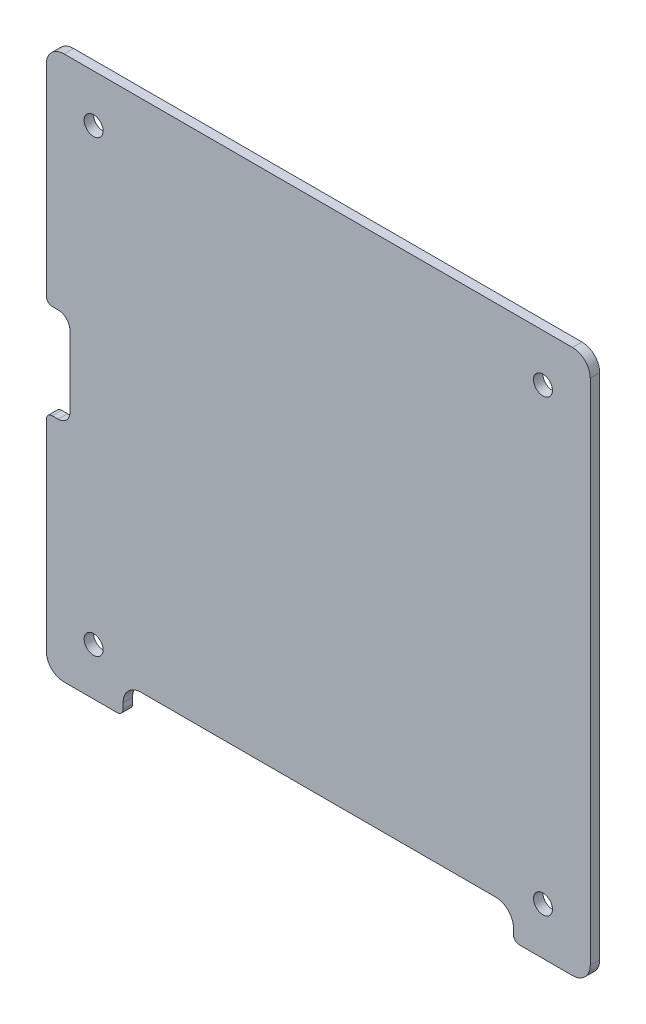
SolidWorks part; units mm, degrees
ref_plane "Front Plane" through (0, 0, 0) normal (0, 0, 1) x (1, 0, 0)
ref_plane "Top Plane" through (0, 0, 0) normal (0, 1, 0) x (1, 0, 0)
ref_plane "Right Plane" through (0, 0, 0) normal (1, 0, 0) x (0, 0, -1)
sketch "Sketch1" plane through (0, 0, 0) normal (0, 0, 1) x (1, 0, 0)
  line L0 (-72.5, 0.75) -> (-72.5, 5.75)
  line L1 (6.5, 92.75) -> (-85.5, 92.75)
  line L2 (6.5, 92.75) -> (6.5, 0.75)
  line L3 (6.5, 0.75) -> (-6.5, 0.75)
  line L4 (-85.5, 92.75) -> (-85.5, 54.75)
  line L5 (-39.5, 92.75) -> (-39.5, 5.75) construction
  line L6 (-72.5, 5.75) -> (-6.5, 5.75)
  line L7 (-6.5, 5.75) -> (-6.5, 0.75)
  line L8 (-72.5, 0.75) -> (-85.5, 0.75)
  line L9 (-81.5, 43.75) -> (6.5, 43.75) construction
  line L10 (-85.5, 54.75) -> (-81.5, 54.75)
  line L11 (-81.5, 54.75) -> (-81.5, 38.75)
  line L12 (-81.5, 38.75) -> (-85.5, 38.75)
  line L13 (-85.5, 38.75) -> (-85.5, 0.75)
  point P8 (-37.5, 43.75)
  dimension "D1" = 46
  dimension "D2" = 5
  dimension "D3" = 49
  dimension "D4" = 33
  dimension "D5" = 33
  dimension "D6" = 92
  dimension "D7" = 92
  dimension "D8" = 4
  dimension "D9" = 38
  dimension "D10" = 16
extrude "Boss-Extrude1" add sketch "Sketch1" against normal blind 1.6
hole_wizard "Ø3.2 (3.2) Diameter Hole1" positions "Sketch6" profile "Sketch5" hole size "Ø3.2" standard "Ansi Metric" end condition up to next
sketch "Sketch6" plane through (0, 0, -1.6) normal (0, 0, -1) x (-1, 0, 0)
  line L5 (81.5, 46.75) -> (-6.5, 46.75) construction
  line L7 (-6.5, 0.75) -> (-6.5, 92.75) construction
  line L9 (39.5, 92.75) -> (39.5, 5.75) construction
  line L10 (-6.5, 92.75) -> (85.5, 92.75) construction
  line L11 (72.5, 5.75) -> (6.5, 5.75) construction
  line L12 (81.5, 54.75) -> (81.5, 38.75) construction
  point P1 (1.5, 84.75)
  point P4 (1.5, 8.75)
  point P7 (77.5, 8.75)
  point P10 (77.5, 84.75)
  dimension "D1" = 38
  dimension "D2" = 38
  dimension "D3" = 38
  dimension "D4" = 38
  dimension "D5" = 38
  dimension "D6" = 38
  dimension "D7" = 38
  dimension "D8" = 38
sketch "Sketch5" plane through (-1.5, 84.75, -1.6) normal (1, 0, 0) x (0, 1, 0)
  line L0 (0, 0) -> (0, 1.6)
  line L1 (0, 1.6) -> (1.6, 1.6)
  line L2 (1.6, 1.6) -> (1.6, 0)
  line L5 (1.6, 0) -> (0, 0)
  line L11 (0, -6.35) -> (0, 107.95) construction
  dimension "Thru Hole Dia." = 3.2
  dimension "Thru Hole Depth" = 1.6
fillet "Fillet1" radius 3 6 edges at (-6.5, 5.75, -0.8) (-72.5, 5.75, -0.8) (6.5, 0.75, -0.8) (-85.5, 92.75, -0.8) (6.5, 92.75, -0.8) (-85.5, 0.75, -0.8)
fillet "Fillet2" radius 1 4 edges at (-6.5, 0.75, -0.8) (-72.5, 0.75, -0.8) (-85.5, 38.75, -0.8) (-85.5, 54.75, -0.8)
sketch "Sketch7" [suppressed] plane through (0, 0, 0) normal (0, 0, 1) x (1, 0, 0)
  line L0 (-77.5, 84.75) -> (-77.5, 8.75) construction
  line L1 (-77.5, 46.75) -> (-60.6017, 46.75) construction
fillet "Fillet3" radius 2 2 edges at (-81.5, 38.75, -0.8) (-81.5, 54.75, -0.8)
